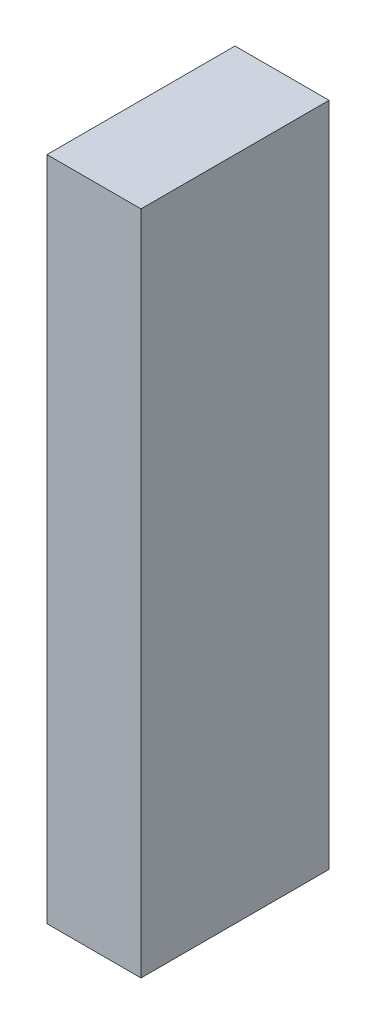
SolidWorks part; units mm, degrees
ref_plane "Front Plane" through (0, 0, 0) normal (0, 0, 1) x (1, 0, 0)
ref_plane "Top Plane" through (0, 0, 0) normal (0, 1, 0) x (1, 0, 0)
ref_plane "Right Plane" through (0, 0, 0) normal (1, 0, 0) x (0, 0, -1)
ref_plane "PL_Board_base" through (0, 0, 30) normal (0, 0, 1) x (1, 0, 0)
sketch "SK_Board" plane through (0, 0, 30) normal (0, 0, 1) x (1, 0, 0)
  line L0 (55, -42.5) -> (67, -42.5)
  line L1 (67, -42.5) -> (67, 42.5)
  line L2 (67, 42.5) -> (55, 42.5)
  line L3 (55, 42.5) -> (55, -42.5)
  dimension "P1" = 55
  dimension "P2" = 42.5
  dimension "P3" = 67
  dimension "P4" = 42.5
  dimension "P5" = 67
  dimension "P6" = 42.5
  dimension "P7" = 55
  dimension "P8" = 42.5
extrude "Board" add sketch "SK_Board" along normal blind 24
